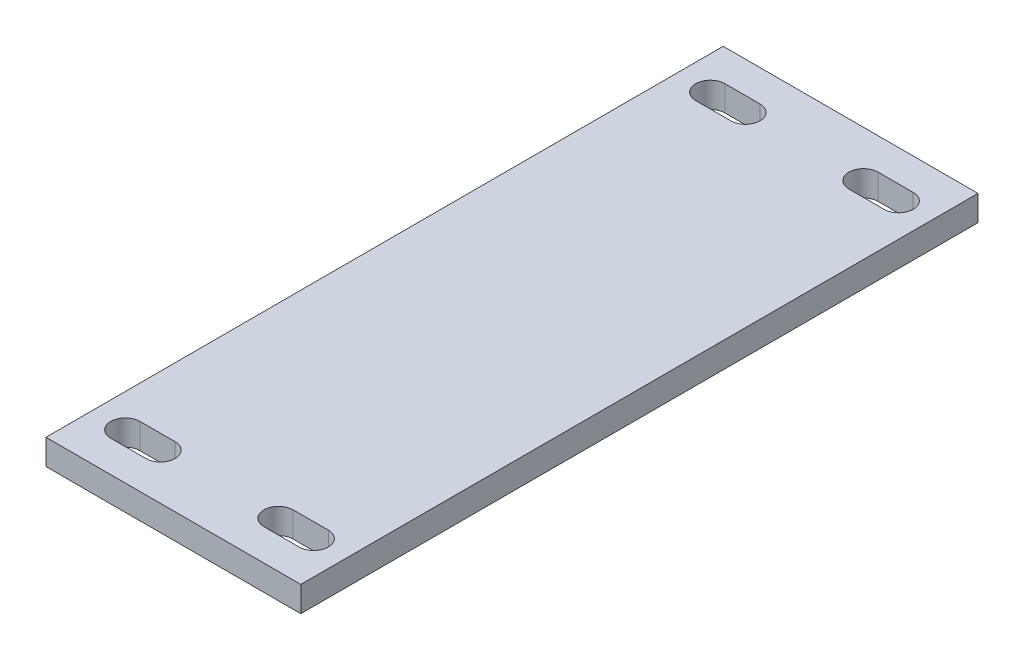
SolidWorks part; units mm, degrees
ref_plane "Front Plane" through (0, 0, 0) normal (0, 0, 1) x (1, 0, 0)
ref_plane "Top Plane" through (0, 0, 0) normal (0, 1, 0) x (1, 0, 0)
ref_plane "Right Plane" through (0, 0, 0) normal (1, 0, 0) x (0, 0, -1)
sketch "Sketch1" plane through (0, 0, 0) normal (0, 1, 0) x (1, 0, 0)
  line L0 (30.1, 160) -> (30.1, 0) construction
  line L1 (0, 0) -> (60.2, 0)
  line L2 (0, 0) -> (0, 160)
  line L3 (0, 160) -> (60.2, 160)
  line L4 (60.2, 0) -> (60.2, 160)
  line L5 (7.85, 152.55) -> (16.15, 152.55)
  line L7 (7.85, 145.65) -> (16.15, 145.65)
  line L9 (60.2, 80) -> (0, 80) construction
  line L10 (52.35, 145.65) -> (44.05, 145.65)
  line L11 (52.35, 152.55) -> (44.05, 152.55)
  line L12 (52.35, 7.45) -> (44.05, 7.45)
  line L13 (52.35, 14.35) -> (44.05, 14.35)
  line L14 (7.85, 14.35) -> (16.15, 14.35)
  line L15 (7.85, 7.45) -> (16.15, 7.45)
  line L16 (16.15, 149.1) -> (16.15, 10.9) construction
  line L17 (16.15, 149.1) -> (44.05, 149.1) construction
  arc A0 (7.85, 152.55) -> (7.85, 145.65) centre (7.85, 149.1) ccw
  arc A1 (16.15, 145.65) -> (16.15, 152.55) centre (16.15, 149.1) ccw
  arc A2 (52.35, 152.55) -> (52.35, 145.65) centre (52.35, 149.1) cw
  arc A3 (44.05, 145.65) -> (44.05, 152.55) centre (44.05, 149.1) cw
  arc A4 (44.05, 14.35) -> (44.05, 7.45) centre (44.05, 10.9) ccw
  arc A5 (52.35, 7.45) -> (52.35, 14.35) centre (52.35, 10.9) ccw
  arc A6 (7.85, 7.45) -> (7.85, 14.35) centre (7.85, 10.9) cw
  arc A7 (16.15, 14.35) -> (16.15, 7.45) centre (16.15, 10.9) cw
  dimension "D6" = 8.3
  dimension "D4" = 7.85
  dimension "D1" = 60.2
  dimension "D2" = 160
  dimension "D3" = 7.45
  dimension "D5" = 6.9
  dimension "D7" = 27.9
  dimension "D8" = 138.2
extrude "Boss-Extrude1" add sketch "Sketch1" along normal blind 6
sketch "Sketch2" plane through (0, 0, 0) normal (0, -1, 0) x (-1, 0, 0)
  line L0 (-52.35, 152.55) -> (-44.05, 152.55) construction
  line L1 (-44.05, 145.65) -> (-52.35, 145.65) construction
  line L2 (-16.15, 152.55) -> (-7.85, 152.55) construction
  line L3 (-7.85, 145.65) -> (-16.15, 145.65) construction
  line L4 (0, 0) -> (0, 160)
  line L5 (0, 160) -> (-60.2, 160)
  line L6 (-60.2, 160) -> (-60.2, 0)
  line L7 (-60.2, 0) -> (0, 0)
  line L8 (0, 0) -> (0, 160)
  line L9 (0, 160) -> (-60.2, 160)
  line L10 (-60.2, 160) -> (-60.2, 0)
  line L11 (-60.2, 0) -> (0, 0)
  line L12 (-52.35, 14.35) -> (-44.05, 14.35) construction
  line L13 (-44.05, 7.45) -> (-52.35, 7.45) construction
  line L14 (-16.15, 14.35) -> (-7.85, 14.35) construction
  line L15 (-7.85, 7.45) -> (-16.15, 7.45) construction
  line L16 (-52.35, 152.55) -> (-44.05, 152.55)
  line L17 (-44.05, 145.65) -> (-52.35, 145.65)
  line L18 (-16.15, 152.55) -> (-7.85, 152.55)
  line L19 (-7.85, 145.65) -> (-16.15, 145.65)
  line L20 (-52.35, 14.35) -> (-44.05, 14.35)
  line L21 (-44.05, 7.45) -> (-52.35, 7.45)
  line L22 (-16.15, 14.35) -> (-7.85, 14.35)
  line L23 (-7.85, 7.45) -> (-16.15, 7.45)
  arc A0 (-52.35, 152.55) -> (-52.35, 145.65) centre (-52.35, 149.1) ccw construction
  arc A1 (-44.05, 145.65) -> (-44.05, 152.55) centre (-44.05, 149.1) ccw construction
  arc A2 (-7.85, 145.65) -> (-7.85, 152.55) centre (-7.85, 149.1) ccw construction
  arc A3 (-16.15, 152.55) -> (-16.15, 145.65) centre (-16.15, 149.1) ccw construction
  arc A4 (-52.35, 14.35) -> (-52.35, 7.45) centre (-52.35, 10.9) ccw construction
  arc A5 (-44.05, 7.45) -> (-44.05, 14.35) centre (-44.05, 10.9) ccw construction
  arc A6 (-16.15, 14.35) -> (-16.15, 7.45) centre (-16.15, 10.9) ccw construction
  arc A7 (-7.85, 7.45) -> (-7.85, 14.35) centre (-7.85, 10.9) ccw construction
  arc A8 (-52.35, 152.55) -> (-52.35, 145.65) centre (-52.35, 149.1) ccw
  arc A9 (-44.05, 145.65) -> (-44.05, 152.55) centre (-44.05, 149.1) ccw
  arc A10 (-7.85, 145.65) -> (-7.85, 152.55) centre (-7.85, 149.1) ccw
  arc A11 (-16.15, 152.55) -> (-16.15, 145.65) centre (-16.15, 149.1) ccw
  arc A12 (-52.35, 14.35) -> (-52.35, 7.45) centre (-52.35, 10.9) ccw
  arc A13 (-44.05, 7.45) -> (-44.05, 14.35) centre (-44.05, 10.9) ccw
  arc A14 (-16.15, 14.35) -> (-16.15, 7.45) centre (-16.15, 10.9) ccw
  arc A15 (-7.85, 7.45) -> (-7.85, 14.35) centre (-7.85, 10.9) ccw
  dimension "D1" = 0
